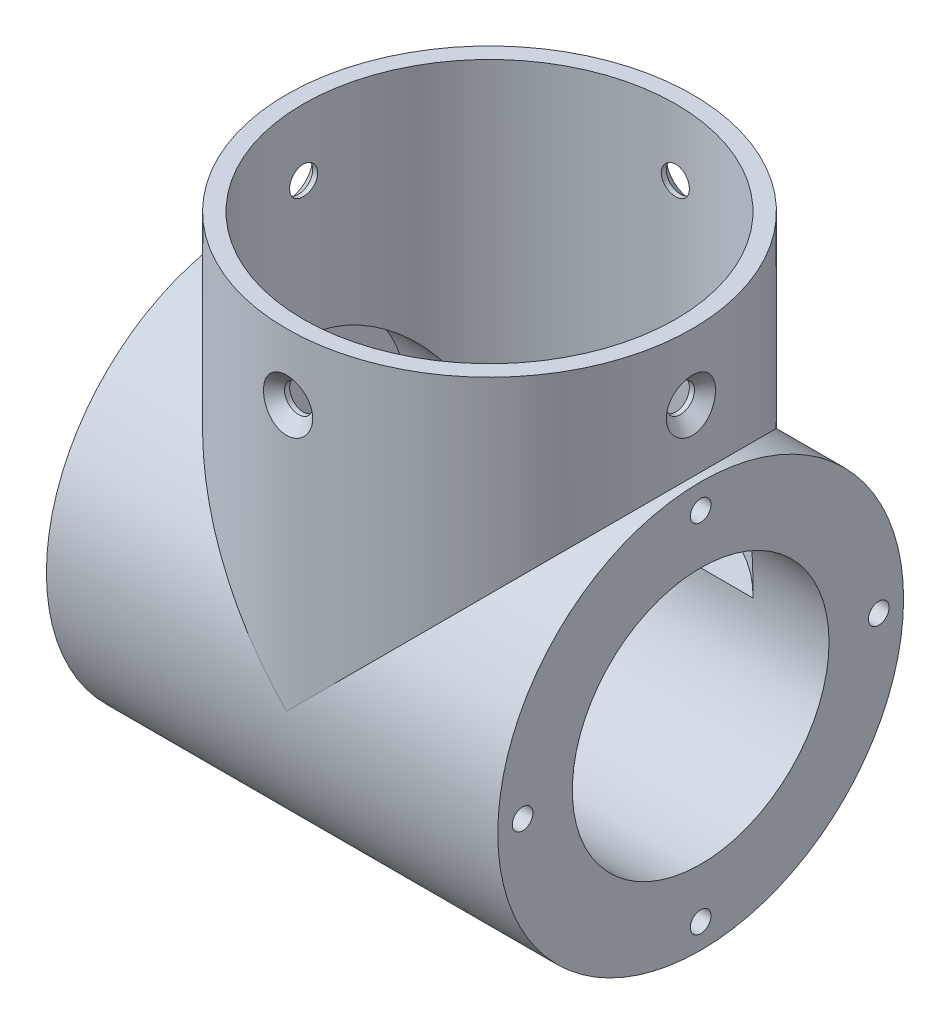
SolidWorks part; units mm, degrees
ref_plane "Спереди" through (0, 0, 0) normal (0, 0, 1) x (1, 0, 0)
ref_plane "Сверху" through (0, 0, 0) normal (0, 1, 0) x (1, 0, 0)
ref_plane "Справа" through (0, 0, 0) normal (1, 0, 0) x (0, 0, -1)
sketch "Эскиз1" plane through (0, 0, 0) normal (1, 0, 0) x (0, 0, -1)
  circle A0 centre (0, 0) radius 24.5
  dimension "D1" = 49
extrude "Бобышка-Вытянуть1" add sketch "Эскиз1" along normal blind 55
sketch "Эскиз2" plane through (0, 0, 0) normal (0, 1, 0) x (1, 0, 0)
  circle A0 centre (29.5, 0) radius 24.5
  dimension "D1" = 49
  dimension "D2" = 29.5
extrude "Бобышка-Вытянуть2" add sketch "Эскиз2" along normal blind 40
sketch "Эскиз3" plane through (55, 0, 0) normal (1, 0, 0) x (0, 0, -1)
  circle A0 centre (0, 0) radius 15.5
  dimension "D1" = 31
extrude "Вырез-Вытянуть1" cut sketch "Эскиз3" against normal blind 51
sketch "Эскиз4" plane through (0, 0, 0) normal (-1, 0, 0) x (0, 0, 1)
  circle A0 centre (7, 0) radius 1.5
  dimension "D2" = 3
  dimension "D1" = 7
extrude "Вырез-Вытянуть2" cut sketch "Эскиз4" against normal through all
pattern_circular "Круговой массив1" count 4 over 360 about axis through (0, 0, 0) along (1, 0, 0) of "Вырез-Вытянуть2"
sketch "Эскиз5" plane through (0, 40, 0) normal (0, 1, 0) x (1, 0, 0)
  circle A0 centre (29.5, 0) radius 22.5
  dimension "D2" = 45
  dimension "D1" = 29.5
extrude "Вырез-Вытянуть3" cut sketch "Эскиз5" against normal blind 40
hole_wizard "Зенковка для винта с полупотайной головкой M31" positions "Трехмерный эскиз2" profile "Эскиз10" countersink size "M3" standard "DIN"
sketch3d "Трехмерный эскиз2"
  line L0 (54, 32, 0) -> (54, 40, 0)
  line L1 (54, 40, 0) -> (29.5, 40, 0)
  line L2 (29.5, 40, 0) -> (29.5, 0, 0) construction
  circle A0 centre (29.5, 40, 0) radius 24.5 construction
  point P0 (54, 32, 0)
  point P7 (29.5, 64.5, 0)
  dimension "D1" = 8
sketch "Эскиз10" plane through (54, 32, 0) normal (0, 1, 0) x (0, 0, -1)
  line L0 (0, 0) -> (0, 47.001)
  line L1 (0, 47.001) -> (1.7, 47.001)
  line L2 (1.7, 47.001) -> (1.7, 1.45)
  line L3 (1.7, 1.45) -> (3.15, 0)
  line L5 (3.15, 0) -> (0, 0)
  line L6 (-1.7, 1.45) -> (-3.15, 0) construction
  line L11 (0, -6.35) -> (0, 107.95) construction
  dimension "Диаметр сквозного отверстия" = 3.4
  dimension "Глубина сквозного отверстия" = 47.001
  dimension "Диаметр передней зенковки" = 6.3
  dimension "Угол передней зенковки" = 90
pattern_circular "Круговой массив2" count 4 every 90 about axis through (29.5, 40, 0) along (0, 1, 0) of "Зенковка для винта с полупотайной головкой M31"
sketch "Эскиз9" plane through (0, 0, 0) normal (-1, 0, 0) x (0, 0, 1)
  circle A0 centre (0, 0) radius 15
  circle A1 centre (0, 0) radius 24.5
  dimension "D1" = 30
  dimension "D2" = 49
extrude "Вырез-Вытянуть7" cut sketch "Эскиз9" against normal blind 0.5
hole_wizard "Отверстие обработанное метчиком M31" positions "Эскиз11" profile "Эскиз12" tap size "M3" standard "DIN"
sketch "Эскиз11" plane through (55, 0, 0) normal (1, 0, 0) x (0, 0, -1)
  line L0 (0, 0) -> (21.5, 0)
  circle A0 centre (0, 0) radius 21.5
  point P0 (21.5, 0)
  point P12 (0, 0)
  point P13 (21.5, 0)
  dimension "D1" = 43
sketch "Эскиз12" plane through (55, 0, -21.5) normal (0, 1, 0) x (0, 0, -1)
  line L0 (0, 0) -> (0, 8.7511)
  line L1 (0, 8.7511) -> (1.25, 8)
  line L2 (1.25, 8) -> (1.25, 0)
  line L5 (1.25, 0) -> (0, 0)
  line L10 (0, 8.7511) -> (-1.25, 8) construction
  line L11 (0, -6.35) -> (0, 107.95) construction
  dimension "Диаметр сверла" = 2.5
  dimension "Глубина сверла" = 8
  dimension "Угол заточки сверла" = 118
cosmetic thread "Отверстие резьбы1" parameters "D1"=6, "D2"=3
pattern_circular "Круговой массив3" count 4 every 90 about axis through (0, 0, 0) along (1, 0, 0) of "Отверстие обработанное метчиком M31"
